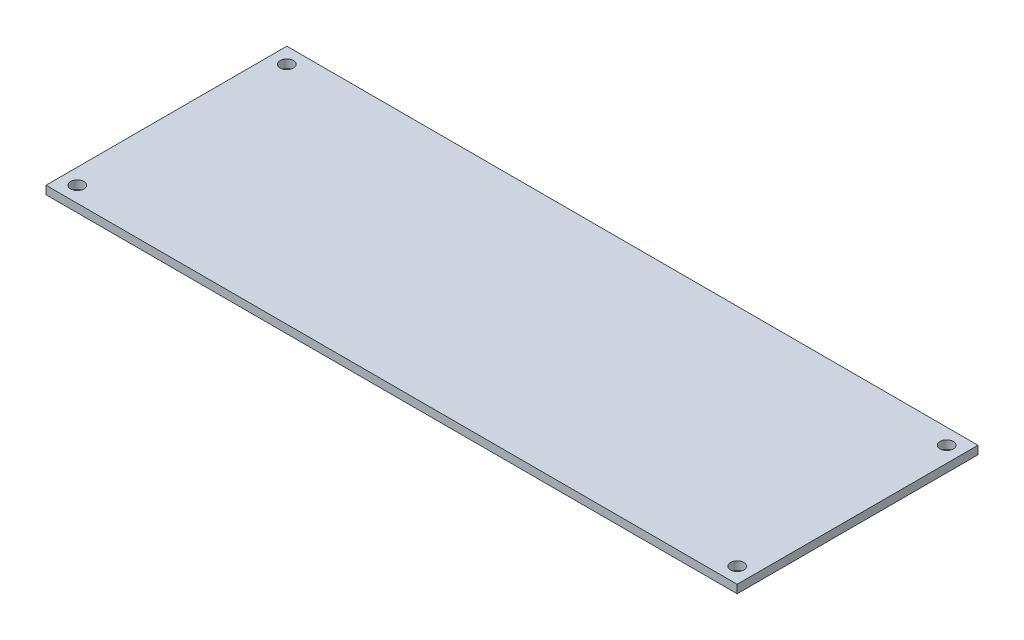
SolidWorks part; units mm, degrees
ref_plane "Front Plane" through (0, 0, 0) normal (0, 0, 1) x (1, 0, 0)
ref_plane "Top Plane" through (0, 0, 0) normal (0, 1, 0) x (1, 0, 0)
ref_plane "Right Plane" through (0, 0, 0) normal (1, 0, 0) x (0, 0, -1)
sketch "Sketch1" plane through (0, 0, 0) normal (0, 1, 0) x (1, 0, 0)
  line L1 (-83.8, 29.2) -> (83.8, 29.2)
  line L2 (-83.8, 29.2) -> (-83.8, -29.2)
  line L3 (-83.8, -29.2) -> (83.8, -29.2)
  line L4 (83.8, 29.2) -> (83.8, -29.2)
  line L5 (-83.8, 29.2) -> (83.8, -29.2) construction
  line L6 (-83.8, -29.2) -> (83.8, 29.2) construction
  point P0 (0, 0)
  dimension "D1" = 58.4
  dimension "D2" = 167.6
extrude "Boss-Extrude1" add sketch "Sketch1" along normal blind 2 contours L1 L4 L3 L2
sketch "Sketch2" plane through (0, 0, 0) normal (0, 1, 0) x (1, 0, 0)
  line L0 (-80, 25.4) -> (-80, -25.4) construction
  line L1 (-80, -25.4) -> (80, -25.4) construction
  circle A0 centre (-80, 25.4) radius 1.6
  circle A1 centre (-80, -25.4) radius 1.6
  circle A2 centre (80, 25.4) radius 1.6
  circle A3 centre (80, -25.4) radius 1.6
  point P8 (-80, 0)
  point P9 (0, -25.4)
  dimension "D1" = 50.8
  dimension "D2" = 3.2
  dimension "D3" = 160
extrude "Cut-Extrude1" cut sketch "Sketch2" along normal through all
